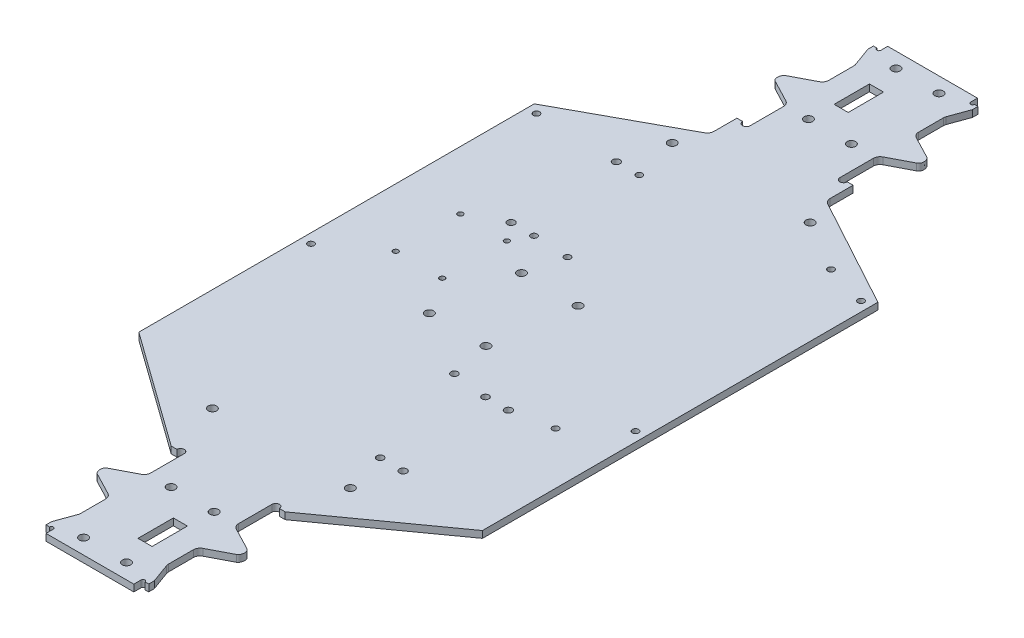
SolidWorks part; units mm, degrees
ref_plane "Front Plane" through (0, 0, 0) normal (0, 0, 1) x (1, 0, 0)
ref_plane "Top Plane" through (0, 0, 0) normal (0, 1, 0) x (1, 0, 0)
ref_plane "Right Plane" through (0, 0, 0) normal (1, 0, 0) x (0, 0, -1)
sketch "Sketch1" plane through (0, 0, 0) normal (0, 1, 0) x (1, 0, 0)
  line L0 (20.9042, 21.0573) -> (20.9042, 9.5003)
  line L1 (-20.9042, 36.9061) -> (20.9042, 36.9061)
  line L2 (0, 36.9061) -> (0, -449.5929) construction
  line L3 (20.9042, 36.9061) -> (20.9042, 33.6803)
  line L4 (22.7076, 33.6803) -> (24.3586, 33.6803)
  line L5 (24.3586, 33.6803) -> (24.3586, 31.1403)
  line L6 (24.3586, 31.1403) -> (21.0944, 22.1398)
  line L7 (20.9042, 7.5746) -> (20.9042, -9.6974) construction
  line L8 (20.9042, -1.0614) -> (34.1122, -1.0614) construction
  line L9 (22.6119, -8.8075) -> (32.9038, -3.4443)
  line L10 (22.6119, 6.6847) -> (32.9038, 1.3215)
  line L11 (20.9042, -11.6231) -> (20.9042, -27.1726)
  line L12 (24.384, -27.1726) -> (27.051, -27.1726)
  line L13 (27.051, -27.1726) -> (27.051, -37.8598)
  line L14 (28.7069, -40.6479) -> (80.01, -68.6007)
  line L15 (80.01, -68.6007) -> (80.01, -252.7507)
  line L16 (26.5303, -291.1425) -> (80.01, -252.7507)
  line L17 (26.5303, -291.1425) -> (23.8379, -291.1425)
  line L19 (20.4343, -306.692) -> (20.4343, -291.1425)
  line L20 (20.4515, -355.5288) -> (-20.4515, -355.5288)
  line L21 (-20.4343, -339.3725) -> (-20.4343, -327.8155)
  line L22 (22.142, -324.9998) -> (32.4339, -319.6366)
  line L23 (22.142, -309.5077) -> (32.4339, -314.8709)
  line L24 (23.8887, -349.4554) -> (20.6245, -340.4549)
  line L25 (23.8834, -351.9954) -> (23.8887, -349.4554)
  line L26 (22.2377, -352.1279) -> (23.8834, -351.9954)
  line L27 (20.4515, -355.5288) -> (20.4515, -352.303)
  line L28 (-20.4515, -355.5288) -> (-20.4515, -352.303)
  line L29 (20.4343, -339.3725) -> (20.4343, -327.8155)
  line L30 (-22.2377, -352.1279) -> (-23.8834, -351.9954)
  line L31 (-23.8834, -351.9954) -> (-23.8887, -349.4554)
  line L32 (-23.8887, -349.4554) -> (-20.6245, -340.4549)
  line L33 (-22.142, -309.5077) -> (-32.4339, -314.8709)
  line L34 (-22.142, -324.9998) -> (-32.4339, -319.6366)
  line L35 (-20.4343, -306.692) -> (-20.4343, -291.1425)
  line L36 (-26.5303, -291.1425) -> (-23.8379, -291.1425)
  line L37 (-26.5303, -291.1425) -> (-80.01, -252.7507)
  line L38 (-80.01, -68.6007) -> (-80.01, -252.7507)
  line L39 (-28.7069, -40.6479) -> (-80.01, -68.6007)
  line L40 (-27.051, -27.1726) -> (-27.051, -37.8598)
  line L41 (-24.384, -27.1726) -> (-27.051, -27.1726)
  line L42 (-20.9042, -11.6231) -> (-20.9042, -27.1726)
  line L43 (-20.9042, 36.9061) -> (-20.9042, 33.6803)
  line L44 (-20.9042, -1.0614) -> (-34.1122, -1.0614) construction
  line L45 (-20.9042, 7.5746) -> (-20.9042, -9.6974) construction
  line L46 (-22.6119, 6.6847) -> (-32.9038, 1.3215)
  line L47 (-22.6119, -8.8075) -> (-32.9038, -3.4443)
  line L48 (-24.3586, 31.1403) -> (-21.0944, 22.1398)
  line L49 (-24.3586, 33.6803) -> (-24.3586, 31.1403)
  line L50 (-22.7076, 33.6803) -> (-24.3586, 33.6803)
  line L51 (-20.9042, 21.0573) -> (-20.9042, 9.5003)
  arc A0 (20.9042, 33.6803) -> (22.7076, 33.6803) centre (21.8059, 33.6803) ccw
  arc A1 (20.9042, 21.0573) -> (21.0944, 22.1398) centre (24.0792, 21.0573) cw
  arc A2 (22.6119, 6.6847) -> (20.9042, 9.5003) centre (24.0792, 9.5003) cw
  arc A3 (20.9042, -27.1726) -> (24.384, -27.1726) centre (22.6441, -27.1726) ccw
  arc A4 (28.7069, -40.6479) -> (27.051, -37.8598) centre (30.226, -37.8598) cw
  arc A5 (20.9042, -11.6231) -> (22.6119, -8.8075) centre (24.0792, -11.6231) cw
  arc A6 (23.8379, -291.1425) -> (20.4343, -291.1425) centre (22.1361, -291.1425) ccw
  arc A7 (20.4343, -306.692) -> (22.142, -309.5077) centre (23.6093, -306.692) ccw
  arc A8 (22.142, -324.9998) -> (20.4343, -327.8155) centre (23.6093, -327.8155) ccw
  arc A9 (20.4343, -339.3725) -> (20.6245, -340.4549) centre (23.6093, -339.3725) ccw
  arc A10 (20.4515, -352.303) -> (22.2377, -352.1279) centre (21.336, -352.1279) cw
  arc A11 (-20.4515, -352.303) -> (-22.2377, -352.1279) centre (-21.336, -352.1279) ccw
  arc A12 (-20.4343, -339.3725) -> (-20.6245, -340.4549) centre (-23.6093, -339.3725) cw
  arc A13 (-22.142, -324.9998) -> (-20.4343, -327.8155) centre (-23.6093, -327.8155) cw
  arc A14 (-20.4343, -306.692) -> (-22.142, -309.5077) centre (-23.6093, -306.692) cw
  arc A15 (-23.8379, -291.1425) -> (-20.4343, -291.1425) centre (-22.1361, -291.1425) cw
  arc A16 (-28.7069, -40.6479) -> (-27.051, -37.8598) centre (-30.226, -37.8598) ccw
  arc A17 (-20.9042, -27.1726) -> (-24.384, -27.1726) centre (-22.6441, -27.1726) cw
  arc A18 (-20.9042, -11.6231) -> (-22.6119, -8.8075) centre (-24.0792, -11.6231) ccw
  arc A19 (-22.6119, 6.6847) -> (-20.9042, 9.5003) centre (-24.0792, 9.5003) ccw
  arc A20 (-20.9042, 21.0573) -> (-21.0944, 22.1398) centre (-24.0792, 21.0573) ccw
  arc A21 (-20.9042, 33.6803) -> (-22.7076, 33.6803) centre (-21.8059, 33.6803) cw
  spline S0 degree 3 poles (32.9038, 1.3215) (33.6149, 0.9509) (34.4634, -1.1376) (33.9071, -2.9215) (32.9038, -3.4443) knots 0 0 0 0 0.5 1 1 1 1
  spline S1 degree 3 poles (32.4339, -319.6366) (33.145, -319.2661) (33.9935, -317.1776) (33.4372, -315.3937) (32.4339, -314.8709) knots 0 0 0 0 0.5 1 1 1 1
  spline S2 degree 3 poles (-32.4339, -319.6366) (-33.145, -319.2661) (-33.9935, -317.1776) (-33.4372, -315.3937) (-32.4339, -314.8709) knots 0 0 0 0 0.5 1 1 1 1
  spline S3 degree 3 poles (-32.9038, 1.3215) (-33.6149, 0.9509) (-34.4634, -1.1376) (-33.9071, -2.9215) (-32.9038, -3.4443) knots 0 0 0 0 0.5 1 1 1 1
  point P8 (0, 36.9061)
  point P9 (0, 36.9061)
  point P22 (20.9042, 21.6153)
  point P34 (27.051, -39.7456)
  point P48 (0, -355.5288)
  point P69 (20.9042, -351.3667)
  point P87 (-20.9042, -351.3667)
  point P98 (-27.051, -39.7456)
  point P119 (-20.9042, 21.6153)
  dimension "D3" = 0.9017
  dimension "D10" = 3.175
  dimension "D11" = 3.175
  dimension "D13" = 1.7399
  dimension "D18" = 3.175
  dimension "D19" = 3.175
  dimension "D24" = 1.7018
  dimension "D26" = 3.175
  dimension "D28" = 5.628
  dimension "D30" = 3.175
  dimension "D32" = 3.175
  dimension "D36" = 0.9017
  dimension "D1" = 41.8084
  dimension "D2" = 3.2258
  dimension "D4" = 1.651
  dimension "D5" = 2.54
  dimension "D6" = 12.065
  dimension "D7" = 11.557
  dimension "D8" = 17.272
  dimension "D9" = 13.208
  dimension "D12" = 17.4752
  dimension "D14" = 2.667
  dimension "D15" = 12.573
  dimension "D17" = 80.01
  dimension "D20" = 184.15
  dimension "D22" = 26.5303
  dimension "D23" = 2.6924
  dimension "D25" = 15.5495
  dimension "D27" = 11.6055
  dimension "D29" = 11.6055
  dimension "D31" = 11.557
  dimension "D33" = 9.5741
  dimension "D34" = 2.54
  dimension "D35" = 1.651
  dimension "D37" = 3.2258
extrude "Boss-Extrude1" add sketch "Sketch1" along normal blind 3.175
sketch "Sketch3" plane through (0, 3.175, 0) normal (0, 1, 0) x (1, 0, 0)
  line L0 (0, 45.4183) -> (0, -355.5288) construction
  line L1 (20.9042, 36.9061) -> (-20.9042, 36.9061) construction
  line L2 (-20.4515, -355.5288) -> (20.4515, -355.5288) construction
  line L3 (-80.01, -68.6007) -> (-80.01, -252.7507) construction
  line L4 (-9.9822, 17.4751) -> (-3.429, 17.4751)
  line L5 (-9.9822, 17.4751) -> (-9.9822, 1.0159)
  line L6 (-9.9822, 1.0159) -> (-3.429, 1.0159)
  line L7 (-3.429, 17.4751) -> (-3.429, 1.0159)
  line L8 (-20.9042, 21.0573) -> (-20.9042, 9.5003) construction
  line L9 (20.4343, -339.3725) -> (20.4343, -327.8155) construction
  line L10 (2.9591, -319.6386) -> (9.5123, -319.6386)
  line L11 (2.9591, -319.6386) -> (2.9591, -336.0978)
  line L12 (2.9591, -336.0978) -> (9.5123, -336.0978)
  line L13 (9.5123, -319.6386) -> (9.5123, -336.0978)
  line L14 (-75.565, -72.0073) -> (-78.0137, -67.513) construction
  line L15 (-28.7069, -40.6479) -> (-80.01, -68.6007) construction
  line L16 (-28.7069, -40.6479) -> (-80.01, -68.6007) construction
  line L17 (80.01, -252.7507) -> (80.01, -68.6007) construction
  line L18 (-80.01, -68.6007) -> (-80.01, -252.7507) construction
  line L19 (80.01, -252.7507) -> (80.01, -68.6007) construction
  line L20 (20.9042, 36.9061) -> (-20.9042, 36.9061) construction
  line L21 (37.5283, -198.1785) -> (26.8603, -198.1785) construction
  line L22 (23.8379, -291.1425) -> (26.5303, -291.1425) construction
  line L23 (-26.5303, -291.1425) -> (-23.8379, -291.1425) construction
  circle A0 centre (-10.0076, 29.8703) radius 1.9685
  circle A1 centre (10.0076, 29.8703) radius 1.9685
  circle A2 centre (-10.0076, -10.9221) radius 1.9685
  circle A3 centre (10.0076, -10.9221) radius 1.9685
  circle A4 centre (-32.1183, -52.2411) radius 1.9685
  circle A5 centre (32.1183, -52.2411) radius 1.9685
  circle A6 centre (-10.0076, -348.493) radius 1.9685
  circle A7 centre (10.0076, -348.493) radius 1.9685
  circle A8 centre (10.0076, -307.7006) radius 1.9685
  circle A9 centre (-10.0076, -307.7006) radius 1.9685
  circle A10 centre (-32.1183, -266.3816) radius 1.9685
  circle A11 centre (32.1183, -266.3816) radius 1.9685
  circle A12 centre (-37.5283, -72.8405) radius 1.7018
  circle A13 centre (-26.8603, -72.8405) radius 1.4605
  circle A14 centre (-26.8603, -121.8625) radius 1.4605
  circle A15 centre (-37.5283, -121.8625) radius 1.7018
  circle A16 centre (37.5283, -247.2005) radius 1.7018
  circle A17 centre (26.8603, -247.2005) radius 1.5875
  circle A18 centre (37.5283, -198.1785) radius 1.7018
  circle A19 centre (26.8603, -198.1785) radius 1.5875
  circle A20 centre (-10.4544, -122.6597) radius 1.4605
  circle A21 centre (10.2321, -196.0369) radius 1.5875
  circle A22 centre (-14.7308, -139.8231) radius 1.9685
  circle A23 centre (11.6344, -139.8231) radius 1.9685
  circle A24 centre (6.3922, -177.4838) radius 1.9685
  circle A25 centre (-19.973, -177.4838) radius 1.9685
  circle A26 centre (75.565, -72.0073) radius 1.4605
  circle A27 centre (-75.565, -72.0073) radius 1.4605
  circle A28 centre (-75.565, -177.0363) radius 1.4605
  circle A29 centre (75.565, -177.0363) radius 1.4605
  circle A30 centre (55.88, -66.2933) radius 1.4732
  circle A31 centre (55.88, -194.5633) radius 1.4732
  circle A32 centre (-52.7981, -130.2381) radius 1.2065
  circle A33 centre (-31.1065, -130.2381) radius 1.2065
  circle A34 centre (-52.7981, -160.3371) radius 1.2065
  circle A35 centre (-31.1065, -160.3371) radius 1.2065
  dimension "D1" = 3.937
  dimension "D2" = 3.937
  dimension "D5" = 20.0152
  dimension "D6" = 20.0152
  dimension "D7" = 3.937
  dimension "D8" = 64.2366
  dimension "D9" = 46.863
  dimension "D10" = 3.937
  dimension "D11" = 20.0152
  dimension "D12" = 20.0152
  dimension "D15" = 46.863
  dimension "D16" = 64.2366
  dimension "D18" = 3.4036
  dimension "D19" = 2.921
  dimension "D20" = 10.668
  dimension "D21" = 21.2598
  dimension "D22" = 49.022
  dimension "D23" = 10.668
  dimension "D24" = 3.4036
  dimension "D25" = 3.175
  dimension "D17" = 21.2979
  dimension "D26" = 92.964
  dimension "D27" = 10.668
  dimension "D28" = 18.7044
  dimension "D29" = 10.668
  dimension "D30" = 49.022
  dimension "D31" = 2.921
  dimension "D32" = 52.451
  dimension "D33" = 16.4059
  dimension "D34" = 3.175
  dimension "D35" = 16.7655
  dimension "D36" = 19.9294
  dimension "D37" = 3.937
  dimension "D38" = 26.3652
  dimension "D39" = 26.3652
  dimension "D40" = 3.937
  dimension "D41" = 21.6916
  dimension "D42" = 68.072
  dimension "D43" = 3.937
  dimension "D44" = 43.18
  dimension "D45" = 38.0238
  dimension "D46" = 3.937
  dimension "D47" = 16.4592
  dimension "D48" = 6.5532
  dimension "D14" = 40.7924
  dimension "D49" = 40.7924
  dimension "D56" = 2.921
  dimension "D57" = 4.445
  dimension "D58" = 105.029
  dimension "D60" = 5.1181
  dimension "D61" = 90
  dimension "D62" = 2.9464
  dimension "D64" = 128.27
  dimension "D65" = 24.13
  dimension "D66" = 2.9464
  dimension "D67" = 2.413
  dimension "D70" = 20.4442
  dimension "D71" = 9.3905
  dimension "D74" = 2.921
  dimension "D75" = 2.921
  dimension "D76" = 42.4817
  dimension "D3" = 7.0358
  dimension "D13" = 7.0358
  dimension "D50" = 19.431
  dimension "D51" = 10.922
  dimension "D52" = 6.5532
  dimension "D53" = 16.4592
  dimension "D54" = 10.922
  dimension "D55" = 19.431
  dimension "D59" = 105.029
  dimension "D63" = 24.13
  dimension "D68" = 18.9746
  dimension "D69" = 30.099
  dimension "D72" = 160.02
  dimension "D73" = 18.9463
  dimension "D77" = 42.4817
  dimension "D78" = 89.1472
  dimension "D79" = 4.445
  dimension "D80" = 73.6178
  dimension "D81" = 68.3756
  dimension "D82" = 113.6587
extrude "Cut-Extrude1" cut sketch "Sketch3" against normal through all
sketch "Sketch4" [suppressed] plane through (0, 3.175, 0) normal (0, 1, 0) x (1, 0, 0)
  line L0 (-20.9042, -16.1291) -> (20.9042, -16.1291)
  line L1 (-20.9042, -11.6231) -> (-20.9042, -27.1726) construction
  line L2 (20.9042, -27.1726) -> (20.9042, -11.6231) construction
  line L3 (-20.4343, -302.4936) -> (20.4343, -302.4936)
  line L4 (-20.4343, -291.1425) -> (-20.4343, -306.692) construction
  line L5 (20.4343, -306.692) -> (20.4343, -291.1425) construction
  line L6 (-20.4515, -355.5288) -> (20.4515, -355.5288) construction
  line L7 (20.9042, 36.9061) -> (-20.9042, 36.9061) construction
  dimension "D1" = 53.0352
  dimension "D2" = 53.0352
sketch "Sketch5" [suppressed] plane through (0, 0, 0) normal (0, -1, 0) x (1, 0, 0)
  line L0 (20.4343, 295.855) -> (-20.4343, 295.855) construction
  line L1 (20.4343, 306.692) -> (20.4343, 291.1425) construction
  line L2 (-20.4343, 291.1425) -> (-20.4343, 306.692) construction
  line L3 (20.9042, 19.3979) -> (-20.9042, 19.3979) construction
  line L4 (20.9042, 27.1726) -> (20.9042, 11.6231) construction
  line L5 (-20.9042, 11.6231) -> (-20.9042, 27.1726) construction
  line L6 (0, 19.3979) -> (0, 295.855) construction
